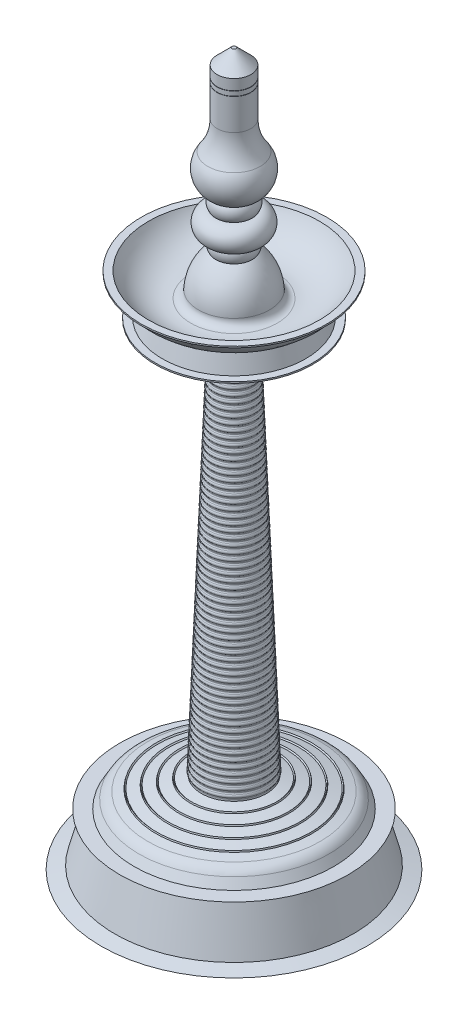
SolidWorks part; units mm, degrees
material "Brass"
ref_plane "Front Plane" through (0, 0, 0) normal (0, 0, 1) x (1, 0, 0)
ref_plane "Top Plane" through (0, 0, 0) normal (0, 1, 0) x (1, 0, 0)
ref_plane "Right Plane" through (0, 0, 0) normal (1, 0, 0) x (0, 0, -1)
sketch "Sketch1" plane through (0, 0, 0) normal (0, 0, 1) x (1, 0, 0)
  line L0 (0, 0) -> (0, 1500)
  line L1 (0, 0) -> (280, 0)
  line L2 (280, 0) -> (251.0222, 7.7646)
  line L3 (251.0222, 7.7646) -> (224.2273, 107.7646)
  line L4 (224.2273, 107.7646) -> (240.5603, 110.6445)
  line L5 (240.5603, 110.6445) -> (210.5603, 110.6445)
  line L6 (210.5603, 110.6445) -> (200.3028, 128.411)
  line L7 (182.0867, 142.3887) -> (164.0972, 147.209)
  line L8 (68.5193, 172.819) -> (68.3959, 176.1083)
  line L9 (37.3252, 1004.6625) -> (166.1634, 1004.6625)
  line L10 (166.1634, 1007.6625) -> (151.1634, 1007.6625)
  line L11 (166.1634, 1004.6625) -> (166.1634, 1007.6625)
  line L12 (151.1634, 1007.6625) -> (140.4454, 1047.6625)
  line L13 (187.6071, 1090.0058) -> (195.3379, 1090.0058)
  line L14 (75, 0) -> (68.3959, 176.1083) construction
  line L15 (195.3379, 1090.0058) -> (195.3379, 1093.0058)
  line L16 (195.3379, 1093.0058) -> (180.3379, 1093.0058)
  line L17 (164.0972, 147.209) -> (163.3207, 150.1068)
  line L18 (163.3207, 150.1068) -> (161.1994, 147.9855)
  line L19 (139.1726, 156.5773) -> (137.0513, 154.4559)
  line L20 (139.9491, 153.6795) -> (139.1726, 156.5773)
  line L21 (115.0245, 163.0477) -> (112.9031, 160.9264)
  line L22 (115.8009, 160.15) -> (115.0245, 163.0477)
  line L23 (90.8763, 169.5182) -> (88.755, 167.3969)
  line L24 (91.6528, 166.6204) -> (90.8763, 169.5182)
  line L25 (163.3207, 150.1068) -> (139.1726, 156.5773) construction
  line L26 (88.755, 167.3969) -> (68.5193, 172.819)
  line L27 (112.9031, 160.9264) -> (91.6528, 166.6204)
  line L28 (137.0513, 154.4559) -> (115.8009, 160.15)
  line L29 (161.1994, 147.9855) -> (139.9491, 153.6795)
  line L30 (0, 1500) -> (4.1464, 1500)
  line L31 (4.1464, 1500) -> (35.5592, 1468.5872)
  line L32 (35.5592, 1468.5872) -> (35.5592, 1446.3854)
  line L33 (37.3674, 1003.5367) -> (37.3252, 1004.6625)
  line L34 (37.4424, 1001.536) -> (0, 2000) construction
  line L35 (38.7061, 994.5731) -> (39.1839, 981.8321) construction
  line L36 (37.8452, 990.7957) -> (37.7424, 993.536) construction
  line L37 (37.8452, 990.7957) -> (37.8174, 991.5352)
  line L38 (38.323, 978.0547) -> (38.2952, 978.7941)
  line L39 (38.323, 978.0547) -> (38.2952, 978.7941) construction
  line L40 (38.8007, 965.3136) -> (38.773, 966.0531)
  line L41 (38.8007, 965.3136) -> (38.773, 966.0531) construction
  line L42 (39.2785, 952.5726) -> (39.2508, 953.312)
  line L43 (39.2785, 952.5726) -> (39.2508, 953.312) construction
  line L44 (39.7563, 939.8315) -> (39.7286, 940.571)
  line L45 (39.7563, 939.8315) -> (39.7286, 940.571) construction
  line L46 (40.2341, 927.0905) -> (40.2064, 927.83)
  line L47 (40.2341, 927.0905) -> (40.2064, 927.83) construction
  line L48 (40.7119, 914.3494) -> (40.6842, 915.0889) construction
  line L49 (40.7119, 914.3494) -> (40.6842, 915.0889)
  line L50 (41.1897, 901.6084) -> (41.162, 902.3479)
  line L51 (41.1897, 901.6084) -> (41.162, 902.3479) construction
  line L52 (41.6675, 888.8673) -> (41.6397, 889.6068)
  line L53 (41.6675, 888.8673) -> (41.6397, 889.6068) construction
  line L54 (42.1453, 876.1263) -> (42.1175, 876.8658) construction
  line L55 (42.1453, 876.1263) -> (42.1175, 876.8658)
  line L56 (42.6231, 863.3852) -> (42.5953, 864.1247)
  line L57 (42.6231, 863.3852) -> (42.5953, 864.1247) construction
  line L58 (43.1008, 850.6442) -> (43.0731, 851.3837)
  line L59 (43.1008, 850.6442) -> (43.0731, 851.3837) construction
  line L60 (43.5786, 837.9032) -> (43.5509, 838.6426) construction
  line L61 (43.5786, 837.9032) -> (43.5509, 838.6426)
  line L62 (44.0564, 825.1621) -> (44.0287, 825.9016) construction
  line L63 (44.0564, 825.1621) -> (44.0287, 825.9016)
  line L64 (44.5342, 812.4211) -> (44.5065, 813.1606) construction
  line L65 (44.5342, 812.4211) -> (44.5065, 813.1606)
  line L66 (45.012, 799.68) -> (44.9843, 800.4195)
  line L67 (45.012, 799.68) -> (44.9843, 800.4195) construction
  line L68 (45.4898, 786.939) -> (45.4621, 787.6785)
  line L69 (45.4898, 786.939) -> (45.4621, 787.6785) construction
  line L70 (45.9676, 774.1979) -> (45.9398, 774.9374) construction
  line L71 (45.9676, 774.1979) -> (45.9398, 774.9374)
  line L72 (46.4454, 761.4569) -> (46.4176, 762.1964)
  line L73 (46.4454, 761.4569) -> (46.4176, 762.1964) construction
  line L74 (46.9232, 748.7158) -> (46.8954, 749.4553)
  line L75 (46.9232, 748.7158) -> (46.8954, 749.4553) construction
  line L76 (47.4009, 735.9748) -> (47.3732, 736.7143)
  line L77 (47.4009, 735.9748) -> (47.3732, 736.7143) construction
  line L78 (47.8787, 723.2338) -> (47.851, 723.9732)
  line L79 (47.8787, 723.2338) -> (47.851, 723.9732) construction
  line L80 (48.3565, 710.4927) -> (48.3288, 711.2322)
  line L81 (48.3565, 710.4927) -> (48.3288, 711.2322) construction
  line L82 (48.8343, 697.7517) -> (48.8066, 698.4912)
  line L83 (48.8343, 697.7517) -> (48.8066, 698.4912) construction
  line L84 (49.3121, 685.0106) -> (49.2844, 685.7501)
  line L85 (49.3121, 685.0106) -> (49.2844, 685.7501) construction
  line L86 (49.7899, 672.2696) -> (49.7622, 673.0091) construction
  line L87 (49.7899, 672.2696) -> (49.7622, 673.0091)
  line L88 (50.2677, 659.5285) -> (50.2399, 660.268)
  line L89 (50.2677, 659.5285) -> (50.2399, 660.268) construction
  line L90 (50.7455, 646.7875) -> (50.7177, 647.527)
  line L91 (50.7455, 646.7875) -> (50.7177, 647.527) construction
  line L92 (51.2233, 634.0464) -> (51.1955, 634.7859)
  line L93 (51.2233, 634.0464) -> (51.1955, 634.7859) construction
  line L94 (51.701, 621.3054) -> (51.6733, 622.0449) construction
  line L95 (51.701, 621.3054) -> (51.6733, 622.0449)
  line L96 (52.1788, 608.5644) -> (52.1511, 609.3038)
  line L97 (52.1788, 608.5644) -> (52.1511, 609.3038) construction
  line L98 (52.6566, 595.8233) -> (52.6289, 596.5628)
  line L99 (52.6566, 595.8233) -> (52.6289, 596.5628) construction
  line L100 (53.1344, 583.0823) -> (53.1067, 583.8217)
  line L101 (53.1344, 583.0823) -> (53.1067, 583.8217) construction
  line L102 (53.6122, 570.3412) -> (53.5845, 571.0807)
  line L103 (53.6122, 570.3412) -> (53.5845, 571.0807) construction
  line L104 (54.09, 557.6002) -> (54.0623, 558.3397) construction
  line L105 (54.09, 557.6002) -> (54.0623, 558.3397)
  line L106 (54.5678, 544.8591) -> (54.5401, 545.5986) construction
  line L107 (54.5678, 544.8591) -> (54.5401, 545.5986)
  line L108 (55.0456, 532.1181) -> (55.0178, 532.8576)
  line L109 (55.0456, 532.1181) -> (55.0178, 532.8576) construction
  line L110 (55.5234, 519.377) -> (55.4956, 520.1165)
  line L111 (55.5234, 519.377) -> (55.4956, 520.1165) construction
  line L112 (56.0011, 506.636) -> (55.9734, 507.3755)
  line L113 (56.0011, 506.636) -> (55.9734, 507.3755) construction
  line L114 (56.4789, 493.895) -> (56.4512, 494.6344)
  line L115 (56.4789, 493.895) -> (56.4512, 494.6344) construction
  line L116 (56.9567, 481.1539) -> (56.929, 481.8934)
  line L117 (56.9567, 481.1539) -> (56.929, 481.8934) construction
  line L118 (57.4345, 468.4129) -> (57.4068, 469.1523) construction
  line L119 (57.4345, 468.4129) -> (57.4068, 469.1523)
  line L120 (57.9123, 455.6718) -> (57.8846, 456.4113) construction
  line L121 (57.9123, 455.6718) -> (57.8846, 456.4113)
  line L122 (58.3901, 442.9308) -> (58.3624, 443.6703) construction
  line L123 (58.3901, 442.9308) -> (58.3624, 443.6703)
  line L124 (58.8679, 430.1897) -> (58.8402, 430.9292) construction
  line L125 (58.8679, 430.1897) -> (58.8402, 430.9292)
  line L126 (59.3457, 417.4487) -> (59.3179, 418.1882)
  line L127 (59.3457, 417.4487) -> (59.3179, 418.1882) construction
  line L128 (59.8235, 404.7076) -> (59.7957, 405.4471) construction
  line L129 (59.8235, 404.7076) -> (59.7957, 405.4471)
  line L130 (60.3013, 391.9666) -> (60.2735, 392.7061) construction
  line L131 (60.3013, 391.9666) -> (60.2735, 392.7061)
  line L132 (60.779, 379.2256) -> (60.7513, 379.965) construction
  line L133 (60.779, 379.2256) -> (60.7513, 379.965)
  line L134 (61.2568, 366.4845) -> (61.2291, 367.224) construction
  line L135 (61.2568, 366.4845) -> (61.2291, 367.224)
  line L136 (61.7346, 353.7435) -> (61.7069, 354.4829)
  line L137 (61.7346, 353.7435) -> (61.7069, 354.4829) construction
  line L138 (62.2124, 341.0024) -> (62.1847, 341.7419) construction
  line L139 (62.2124, 341.0024) -> (62.1847, 341.7419)
  line L140 (62.6902, 328.2614) -> (62.6625, 329.0009) construction
  line L141 (62.6902, 328.2614) -> (62.6625, 329.0009)
  line L142 (63.168, 315.5203) -> (63.1403, 316.2598) construction
  line L143 (63.168, 315.5203) -> (63.1403, 316.2598)
  line L144 (63.6458, 302.7793) -> (63.618, 303.5188) construction
  line L145 (63.6458, 302.7793) -> (63.618, 303.5188)
  line L146 (64.1236, 290.0382) -> (64.0958, 290.7777) construction
  line L147 (64.1236, 290.0382) -> (64.0958, 290.7777)
  line L148 (64.6014, 277.2972) -> (64.5736, 278.0367) construction
  line L149 (64.6014, 277.2972) -> (64.5736, 278.0367)
  line L150 (65.0791, 264.5562) -> (65.0514, 265.2956) construction
  line L151 (65.0791, 264.5562) -> (65.0514, 265.2956)
  line L152 (65.5569, 251.8151) -> (65.5292, 252.5546)
  line L153 (65.5569, 251.8151) -> (65.5292, 252.5546) construction
  line L154 (66.0347, 239.0741) -> (66.007, 239.8135) construction
  line L155 (66.0347, 239.0741) -> (66.007, 239.8135)
  line L156 (66.5125, 226.333) -> (66.4848, 227.0725) construction
  line L157 (66.5125, 226.333) -> (66.4848, 227.0725)
  line L158 (66.9903, 213.592) -> (66.9626, 214.3315) construction
  line L159 (66.9903, 213.592) -> (66.9626, 214.3315)
  line L160 (67.9459, 188.1099) -> (67.9181, 188.8494) construction
  line L161 (67.9459, 188.1099) -> (67.9181, 188.8494)
  line L162 (67.4681, 200.8509) -> (67.4404, 201.5904) construction
  line L163 (67.4681, 200.8509) -> (67.4404, 201.5904)
  line L164 (35.5592, 1446.3854) -> (34.5983, 1446.1086)
  line L165 (34.5983, 1446.1086) -> (35.5592, 1445.8317)
  line L166 (35.5592, 1436.3854) -> (34.5983, 1436.1086)
  line L167 (34.5983, 1436.1086) -> (35.5592, 1435.8317)
  line L168 (35.5592, 1445.8317) -> (35.5592, 1436.3854) construction
  line L169 (35.5592, 1445.8317) -> (35.5592, 1436.3854)
  line L170 (35.5592, 1435.8317) -> (35.5592, 1369.9089)
  arc A0 (140.4454, 1047.6625) -> (187.6071, 1090.0058) centre (122.3281, 1115.2773) ccw
  arc A1 (200.3028, 128.411) -> (182.0867, 142.3887) centre (174.3221, 113.411) ccw
  arc A2 (55.0794, 1310.554) -> (37.3252, 1235.0425) centre (14.1154, 1280.3425) cw
  arc A3 (35.5592, 1369.9089) -> (55.0794, 1310.554) centre (135.5592, 1369.9089) ccw
  arc A4 (37.3252, 1235.0425) -> (38.0549, 1207.6096) centre (18.2342, 1220.8085) cw
  arc A5 (38.0549, 1207.6096) -> (38.3671, 1155.8588) centre (38.211, 1181.7342) cw
  arc A6 (38.3671, 1155.8588) -> (38.3671, 1132.1847) centre (17.118, 1144.0218) cw
  arc A7 (38.3671, 1132.1847) -> (75, 1058.7969) centre (-27.0346, 1053.7014) cw
  arc A8 (75, 1058.7969) -> (90.8763, 1042.3596) centre (91.1568, 1058.5164) ccw
  arc A9 (90.8763, 1042.3596) -> (180.3379, 1093.0058) centre (99.6879, 1131.1306) ccw
  arc A10 (38.4811, 1000.5739) -> (38.7061, 994.5731) centre (34.5983, 997.4237) cw
  arc A11 (38.7061, 994.5731) -> (37.8174, 991.5352) centre (42.8139, 991.7225) ccw
  arc A12 (38.4811, 1000.5739) -> (37.3674, 1003.5367) centre (42.3639, 1003.7241) cw
  arc A13 (39.1839, 981.8321) -> (38.2952, 978.7941) centre (43.2917, 978.9815) ccw
  arc A14 (38.9588, 987.8328) -> (39.1839, 981.8321) centre (35.076, 984.6826) cw
  arc A15 (38.9588, 987.8328) -> (37.8452, 990.7957) centre (42.8416, 990.9831) cw
  arc A16 (39.6617, 969.091) -> (38.773, 966.0531) centre (43.7695, 966.2405) ccw
  arc A17 (39.4366, 975.0918) -> (39.6617, 969.091) centre (35.5538, 971.9416) cw
  arc A18 (39.4366, 975.0918) -> (38.323, 978.0547) centre (43.3194, 978.242) cw
  arc A19 (40.1395, 956.35) -> (39.2508, 953.312) centre (44.2473, 953.4994) ccw
  arc A20 (39.9144, 962.3508) -> (40.1395, 956.35) centre (36.0316, 959.2005) cw
  arc A21 (39.9144, 962.3508) -> (38.8007, 965.3136) centre (43.7972, 965.501) cw
  arc A22 (40.6172, 943.6089) -> (39.7286, 940.571) centre (44.7251, 940.7584) ccw
  arc A23 (40.3922, 949.6097) -> (40.6172, 943.6089) centre (36.5094, 946.4595) cw
  arc A24 (40.3922, 949.6097) -> (39.2785, 952.5726) centre (44.275, 952.7599) cw
  arc A25 (41.095, 930.8679) -> (40.2064, 927.83) centre (45.2029, 928.0173) ccw
  arc A26 (40.87, 936.8687) -> (41.095, 930.8679) centre (36.9872, 933.7185) cw
  arc A27 (40.87, 936.8687) -> (39.7563, 939.8315) centre (44.7528, 940.0189) cw
  arc A28 (41.5728, 918.1268) -> (40.6842, 915.0889) centre (45.6807, 915.2763) ccw
  arc A29 (41.3478, 924.1276) -> (41.5728, 918.1268) centre (37.465, 920.9774) cw
  arc A30 (41.3478, 924.1276) -> (40.2341, 927.0905) centre (45.2306, 927.2778) cw
  arc A31 (42.0506, 905.3858) -> (41.162, 902.3479) centre (46.1584, 902.5352) ccw
  arc A32 (41.8256, 911.3866) -> (42.0506, 905.3858) centre (37.9428, 908.2364) cw
  arc A33 (41.8256, 911.3866) -> (40.7119, 914.3494) centre (45.7084, 914.5368) cw
  arc A34 (42.5284, 892.6448) -> (41.6397, 889.6068) centre (46.6362, 889.7942) ccw
  arc A35 (42.3034, 898.6455) -> (42.5284, 892.6448) centre (38.4206, 895.4953) cw
  arc A36 (42.3034, 898.6455) -> (41.1897, 901.6084) centre (46.1862, 901.7958) cw
  arc A37 (43.0062, 879.9037) -> (42.1175, 876.8658) centre (47.114, 877.0531) ccw
  arc A38 (42.7812, 885.9045) -> (43.0062, 879.9037) centre (38.8984, 882.7543) cw
  arc A39 (42.7812, 885.9045) -> (41.6675, 888.8673) centre (46.664, 889.0547) cw
  arc A40 (43.484, 867.1627) -> (42.5953, 864.1247) centre (47.5918, 864.3121) ccw
  arc A41 (43.259, 873.1634) -> (43.484, 867.1627) centre (39.3762, 870.0132) cw
  arc A42 (43.259, 873.1634) -> (42.1453, 876.1263) centre (47.1418, 876.3137) cw
  arc A43 (43.9618, 854.4216) -> (43.0731, 851.3837) centre (48.0696, 851.5711) ccw
  arc A44 (43.7367, 860.4224) -> (43.9618, 854.4216) centre (39.8539, 857.2722) cw
  arc A45 (43.7367, 860.4224) -> (42.6231, 863.3852) centre (47.6195, 863.5726) cw
  arc A46 (44.4396, 841.6806) -> (43.5509, 838.6426) centre (48.5474, 838.83) ccw
  arc A47 (44.2145, 847.6814) -> (44.4396, 841.6806) centre (40.3317, 844.5311) cw
  arc A48 (44.2145, 847.6814) -> (43.1008, 850.6442) centre (48.0973, 850.8316) cw
  arc A49 (44.9173, 828.9395) -> (44.0287, 825.9016) centre (49.0252, 826.089) ccw
  arc A50 (44.6923, 834.9403) -> (44.9173, 828.9395) centre (40.8095, 831.7901) cw
  arc A51 (44.6923, 834.9403) -> (43.5786, 837.9032) centre (48.5751, 838.0905) cw
  arc A52 (45.3951, 816.1985) -> (44.5065, 813.1606) centre (49.503, 813.3479) ccw
  arc A53 (45.1701, 822.1993) -> (45.3951, 816.1985) centre (41.2873, 819.0491) cw
  arc A54 (45.1701, 822.1993) -> (44.0564, 825.1621) centre (49.0529, 825.3495) cw
  arc A55 (45.8729, 803.4574) -> (44.9843, 800.4195) centre (49.9808, 800.6069) ccw
  arc A56 (45.6479, 809.4582) -> (45.8729, 803.4574) centre (41.7651, 806.308) cw
  arc A57 (45.6479, 809.4582) -> (44.5342, 812.4211) centre (49.5307, 812.6084) cw
  arc A58 (46.3507, 790.7164) -> (45.4621, 787.6785) centre (50.4585, 787.8658) ccw
  arc A59 (46.1257, 796.7172) -> (46.3507, 790.7164) centre (42.2429, 793.567) cw
  arc A60 (46.1257, 796.7172) -> (45.012, 799.68) centre (50.0085, 799.8674) cw
  arc A61 (46.8285, 777.9754) -> (45.9398, 774.9374) centre (50.9363, 775.1248) ccw
  arc A62 (46.6035, 783.9761) -> (46.8285, 777.9754) centre (42.7207, 780.8259) cw
  arc A63 (46.6035, 783.9761) -> (45.4898, 786.939) centre (50.4863, 787.1264) cw
  arc A64 (47.3063, 765.2343) -> (46.4176, 762.1964) centre (51.4141, 762.3837) ccw
  arc A65 (47.0813, 771.2351) -> (47.3063, 765.2343) centre (43.1985, 768.0849) cw
  arc A66 (47.0813, 771.2351) -> (45.9676, 774.1979) centre (50.9641, 774.3853) cw
  arc A67 (47.7841, 752.4933) -> (46.8954, 749.4553) centre (51.8919, 749.6427) ccw
  arc A68 (47.5591, 758.494) -> (47.7841, 752.4933) centre (43.6763, 755.3438) cw
  arc A69 (47.5591, 758.494) -> (46.4454, 761.4569) centre (51.4419, 761.6443) cw
  arc A70 (48.2619, 739.7522) -> (47.3732, 736.7143) centre (52.3697, 736.9017) ccw
  arc A71 (48.0368, 745.753) -> (48.2619, 739.7522) centre (44.154, 742.6028) cw
  arc A72 (48.0368, 745.753) -> (46.9232, 748.7158) centre (51.9196, 748.9032) cw
  arc A73 (48.7397, 727.0112) -> (47.851, 723.9732) centre (52.8475, 724.1606) ccw
  arc A74 (48.5146, 733.012) -> (48.7397, 727.0112) centre (44.6318, 729.8617) cw
  arc A75 (48.5146, 733.012) -> (47.4009, 735.9748) centre (52.3974, 736.1622) cw
  arc A76 (49.2175, 714.2701) -> (48.3288, 711.2322) centre (53.3253, 711.4196) ccw
  arc A77 (48.9924, 720.2709) -> (49.2175, 714.2701) centre (45.1096, 717.1207) cw
  arc A78 (48.9924, 720.2709) -> (47.8787, 723.2338) centre (52.8752, 723.4211) cw
  arc A79 (49.6952, 701.5291) -> (48.8066, 698.4912) centre (53.8031, 698.6785) ccw
  arc A80 (49.4702, 707.5299) -> (49.6952, 701.5291) centre (45.5874, 704.3797) cw
  arc A81 (49.4702, 707.5299) -> (48.3565, 710.4927) centre (53.353, 710.6801) cw
  arc A82 (50.173, 688.788) -> (49.2844, 685.7501) centre (54.2809, 685.9375) ccw
  arc A83 (49.948, 694.7888) -> (50.173, 688.788) centre (46.0652, 691.6386) cw
  arc A84 (49.948, 694.7888) -> (48.8343, 697.7517) centre (53.8308, 697.939) cw
  arc A85 (50.6508, 676.047) -> (49.7622, 673.0091) centre (54.7586, 673.1964) ccw
  arc A86 (50.4258, 682.0478) -> (50.6508, 676.047) centre (46.543, 678.8976) cw
  arc A87 (50.4258, 682.0478) -> (49.3121, 685.0106) centre (54.3086, 685.198) cw
  arc A88 (51.1286, 663.306) -> (50.2399, 660.268) centre (55.2364, 660.4554) ccw
  arc A89 (50.9036, 669.3067) -> (51.1286, 663.306) centre (47.0208, 666.1565) cw
  arc A90 (50.9036, 669.3067) -> (49.7899, 672.2696) centre (54.7864, 672.4569) cw
  arc A91 (51.6064, 650.5649) -> (50.7177, 647.527) centre (55.7142, 647.7143) ccw
  arc A92 (51.3814, 656.5657) -> (51.6064, 650.5649) centre (47.4986, 653.4155) cw
  arc A93 (51.3814, 656.5657) -> (50.2677, 659.5285) centre (55.2642, 659.7159) cw
  arc A94 (52.0842, 637.8239) -> (51.1955, 634.7859) centre (56.192, 634.9733) ccw
  arc A95 (51.8592, 643.8246) -> (52.0842, 637.8239) centre (47.9764, 640.6744) cw
  arc A96 (51.8592, 643.8246) -> (50.7455, 646.7875) centre (55.742, 646.9749) cw
  arc A97 (52.562, 625.0828) -> (51.6733, 622.0449) centre (56.6698, 622.2323) ccw
  arc A98 (52.3369, 631.0836) -> (52.562, 625.0828) centre (48.4541, 627.9334) cw
  arc A99 (52.3369, 631.0836) -> (51.2233, 634.0464) centre (56.2197, 634.2338) cw
  arc A100 (53.0398, 612.3418) -> (52.1511, 609.3038) centre (57.1476, 609.4912) ccw
  arc A101 (52.8147, 618.3426) -> (53.0398, 612.3418) centre (48.9319, 615.1923) cw
  arc A102 (52.8147, 618.3426) -> (51.701, 621.3054) centre (56.6975, 621.4928) cw
  arc A103 (53.5176, 599.6007) -> (52.6289, 596.5628) centre (57.6254, 596.7502) ccw
  arc A104 (53.2925, 605.6015) -> (53.5176, 599.6007) centre (49.4097, 602.4513) cw
  arc A105 (53.2925, 605.6015) -> (52.1788, 608.5644) centre (57.1753, 608.7517) cw
  arc A106 (53.9953, 586.8597) -> (53.1067, 583.8217) centre (58.1032, 584.0091) ccw
  arc A107 (53.7703, 592.8605) -> (53.9953, 586.8597) centre (49.8875, 589.7103) cw
  arc A108 (53.7703, 592.8605) -> (52.6566, 595.8233) centre (57.6531, 596.0107) cw
  arc A109 (54.4731, 574.1186) -> (53.5845, 571.0807) centre (58.581, 571.2681) ccw
  arc A110 (54.2481, 580.1194) -> (54.4731, 574.1186) centre (50.3653, 576.9692) cw
  arc A111 (54.2481, 580.1194) -> (53.1344, 583.0823) centre (58.1309, 583.2696) cw
  arc A112 (54.9509, 561.3776) -> (54.0623, 558.3397) centre (59.0588, 558.527) ccw
  arc A113 (54.7259, 567.3784) -> (54.9509, 561.3776) centre (50.8431, 564.2282) cw
  arc A114 (54.7259, 567.3784) -> (53.6122, 570.3412) centre (58.6087, 570.5286) cw
  arc A115 (55.4287, 548.6366) -> (54.5401, 545.5986) centre (59.5365, 545.786) ccw
  arc A116 (55.2037, 554.6373) -> (55.4287, 548.6366) centre (51.3209, 551.4871) cw
  arc A117 (55.2037, 554.6373) -> (54.09, 557.6002) centre (59.0865, 557.7875) cw
  arc A118 (55.9065, 535.8955) -> (55.0178, 532.8576) centre (60.0143, 533.0449) ccw
  arc A119 (55.6815, 541.8963) -> (55.9065, 535.8955) centre (51.7987, 538.7461) cw
  arc A120 (55.6815, 541.8963) -> (54.5678, 544.8591) centre (59.5643, 545.0465) cw
  arc A121 (56.3843, 523.1545) -> (55.4956, 520.1165) centre (60.4921, 520.3039) ccw
  arc A122 (56.1593, 529.1552) -> (56.3843, 523.1545) centre (52.2765, 526.005) cw
  arc A123 (56.1593, 529.1552) -> (55.0456, 532.1181) centre (60.0421, 532.3055) cw
  arc A124 (56.8621, 510.4134) -> (55.9734, 507.3755) centre (60.9699, 507.5628) ccw
  arc A125 (56.637, 516.4142) -> (56.8621, 510.4134) centre (52.7542, 513.264) cw
  arc A126 (56.637, 516.4142) -> (55.5234, 519.377) centre (60.5198, 519.5644) cw
  arc A127 (57.3399, 497.6724) -> (56.4512, 494.6344) centre (61.4477, 494.8218) ccw
  arc A128 (57.1148, 503.6732) -> (57.3399, 497.6724) centre (53.232, 500.5229) cw
  arc A129 (57.1148, 503.6732) -> (56.0011, 506.636) centre (60.9976, 506.8234) cw
  arc A130 (57.8177, 484.9313) -> (56.929, 481.8934) centre (61.9255, 482.0808) ccw
  arc A131 (57.5926, 490.9321) -> (57.8177, 484.9313) centre (53.7098, 487.7819) cw
  arc A132 (57.5926, 490.9321) -> (56.4789, 493.895) centre (61.4754, 494.0823) cw
  arc A133 (58.2954, 472.1903) -> (57.4068, 469.1523) centre (62.4033, 469.3397) ccw
  arc A134 (58.0704, 478.1911) -> (58.2954, 472.1903) centre (54.1876, 475.0408) cw
  arc A135 (58.0704, 478.1911) -> (56.9567, 481.1539) centre (61.9532, 481.3413) cw
  arc A136 (58.7732, 459.4492) -> (57.8846, 456.4113) centre (62.8811, 456.5987) ccw
  arc A137 (58.5482, 465.45) -> (58.7732, 459.4492) centre (54.6654, 462.2998) cw
  arc A138 (58.5482, 465.45) -> (57.4345, 468.4129) centre (62.431, 468.6002) cw
  arc A139 (59.251, 446.7082) -> (58.3624, 443.6703) centre (63.3589, 443.8576) ccw
  arc A140 (59.026, 452.709) -> (59.251, 446.7082) centre (55.1432, 449.5588) cw
  arc A141 (59.026, 452.709) -> (57.9123, 455.6718) centre (62.9088, 455.8592) cw
  arc A142 (59.7288, 433.9671) -> (58.8402, 430.9292) centre (63.8366, 431.1166) ccw
  arc A143 (59.5038, 439.9679) -> (59.7288, 433.9671) centre (55.621, 436.8177) cw
  arc A144 (59.5038, 439.9679) -> (58.3901, 442.9308) centre (63.3866, 443.1181) cw
  arc A145 (60.2066, 421.2261) -> (59.3179, 418.1882) centre (64.3144, 418.3755) ccw
  arc A146 (59.9816, 427.2269) -> (60.2066, 421.2261) centre (56.0988, 424.0767) cw
  arc A147 (59.9816, 427.2269) -> (58.8679, 430.1897) centre (63.8644, 430.3771) cw
  arc A148 (60.6844, 408.4851) -> (59.7957, 405.4471) centre (64.7922, 405.6345) ccw
  arc A149 (60.4594, 414.4858) -> (60.6844, 408.4851) centre (56.5766, 411.3356) cw
  arc A150 (60.4594, 414.4858) -> (59.3457, 417.4487) centre (64.3422, 417.6361) cw
  arc A151 (61.1622, 395.744) -> (60.2735, 392.7061) centre (65.27, 392.8934) ccw
  arc A152 (60.9372, 401.7448) -> (61.1622, 395.744) centre (57.0543, 398.5946) cw
  arc A153 (60.9372, 401.7448) -> (59.8235, 404.7076) centre (64.82, 404.895) cw
  arc A154 (61.64, 383.003) -> (60.7513, 379.965) centre (65.7478, 380.1524) ccw
  arc A155 (61.4149, 389.0038) -> (61.64, 383.003) centre (57.5321, 385.8535) cw
  arc A156 (61.4149, 389.0038) -> (60.3013, 391.9666) centre (65.2977, 392.154) cw
  arc A157 (62.1178, 370.2619) -> (61.2291, 367.224) centre (66.2256, 367.4114) ccw
  arc A158 (61.8927, 376.2627) -> (62.1178, 370.2619) centre (58.0099, 373.1125) cw
  arc A159 (61.8927, 376.2627) -> (60.779, 379.2256) centre (65.7755, 379.4129) cw
  arc A160 (62.5955, 357.5209) -> (61.7069, 354.4829) centre (66.7034, 354.6703) ccw
  arc A161 (62.3705, 363.5217) -> (62.5955, 357.5209) centre (58.4877, 360.3714) cw
  arc A162 (62.3705, 363.5217) -> (61.2568, 366.4845) centre (66.2533, 366.6719) cw
  arc A163 (63.0733, 344.7798) -> (62.1847, 341.7419) centre (67.1812, 341.9293) ccw
  arc A164 (62.8483, 350.7806) -> (63.0733, 344.7798) centre (58.9655, 347.6304) cw
  arc A165 (62.8483, 350.7806) -> (61.7346, 353.7435) centre (66.7311, 353.9308) cw
  arc A166 (63.5511, 332.0388) -> (62.6625, 329.0009) centre (67.659, 329.1882) ccw
  arc A167 (63.3261, 338.0396) -> (63.5511, 332.0388) centre (59.4433, 334.8894) cw
  arc A168 (63.3261, 338.0396) -> (62.2124, 341.0024) centre (67.2089, 341.1898) cw
  arc A169 (64.0289, 319.2977) -> (63.1403, 316.2598) centre (68.1367, 316.4472) ccw
  arc A170 (63.8039, 325.2985) -> (64.0289, 319.2977) centre (59.9211, 322.1483) cw
  arc A171 (63.8039, 325.2985) -> (62.6902, 328.2614) centre (67.6867, 328.4487) cw
  arc A172 (64.5067, 306.5567) -> (63.618, 303.5188) centre (68.6145, 303.7061) ccw
  arc A173 (64.2817, 312.5575) -> (64.5067, 306.5567) centre (60.3989, 309.4073) cw
  arc A174 (64.2817, 312.5575) -> (63.168, 315.5203) centre (68.1645, 315.7077) cw
  arc A175 (64.9845, 293.8157) -> (64.0958, 290.7777) centre (69.0923, 290.9651) ccw
  arc A176 (64.7595, 299.8164) -> (64.9845, 293.8157) centre (60.8767, 296.6662) cw
  arc A177 (64.7595, 299.8164) -> (63.6458, 302.7793) centre (68.6423, 302.9667) cw
  arc A178 (65.4623, 281.0746) -> (64.5736, 278.0367) centre (69.5701, 278.224) ccw
  arc A179 (65.2373, 287.0754) -> (65.4623, 281.0746) centre (61.3545, 283.9252) cw
  arc A180 (65.2373, 287.0754) -> (64.1236, 290.0382) centre (69.1201, 290.2256) cw
  arc A181 (65.9401, 268.3336) -> (65.0514, 265.2956) centre (70.0479, 265.483) ccw
  arc A182 (65.715, 274.3344) -> (65.9401, 268.3336) centre (61.8322, 271.1841) cw
  arc A183 (65.715, 274.3344) -> (64.6014, 277.2972) centre (69.5978, 277.4846) cw
  arc A184 (66.4179, 255.5925) -> (65.5292, 252.5546) centre (70.5257, 252.742) ccw
  arc A185 (66.1928, 261.5933) -> (66.4179, 255.5925) centre (62.31, 258.4431) cw
  arc A186 (66.1928, 261.5933) -> (65.0791, 264.5562) centre (70.0756, 264.7435) cw
  arc A187 (66.8956, 242.8515) -> (66.007, 239.8135) centre (71.0035, 240.0009) ccw
  arc A188 (66.6706, 248.8523) -> (66.8956, 242.8515) centre (62.7878, 245.702) cw
  arc A189 (66.6706, 248.8523) -> (65.5569, 251.8151) centre (70.5534, 252.0025) cw
  arc A190 (67.3734, 230.1104) -> (66.4848, 227.0725) centre (71.4813, 227.2599) ccw
  arc A191 (67.1484, 236.1112) -> (67.3734, 230.1104) centre (63.2656, 232.961) cw
  arc A192 (67.1484, 236.1112) -> (66.0347, 239.0741) centre (71.0312, 239.2614) cw
  arc A193 (67.8512, 217.3694) -> (66.9626, 214.3315) centre (71.9591, 214.5188) ccw
  arc A194 (67.6262, 223.3702) -> (67.8512, 217.3694) centre (63.7434, 220.22) cw
  arc A195 (67.6262, 223.3702) -> (66.5125, 226.333) centre (71.509, 226.5204) cw
  arc A196 (68.329, 204.6283) -> (67.4404, 201.5904) centre (72.4368, 201.7778) ccw
  arc A197 (68.104, 210.6291) -> (68.329, 204.6283) centre (64.2212, 207.4789) cw
  arc A198 (68.104, 210.6291) -> (66.9903, 213.592) centre (71.9868, 213.7793) cw
  arc A199 (68.8068, 191.8873) -> (67.9181, 188.8494) centre (72.9146, 189.0367) ccw
  arc A200 (68.5818, 197.8881) -> (68.8068, 191.8873) centre (64.699, 194.7379) cw
  arc A201 (68.5818, 197.8881) -> (67.4681, 200.8509) centre (72.4646, 201.0383) cw
  arc A202 (69.2846, 179.1463) -> (68.3959, 176.1083) centre (73.3924, 176.2957) ccw
  arc A203 (69.0596, 185.147) -> (69.2846, 179.1463) centre (65.1768, 181.9968) cw
  arc A204 (69.0596, 185.147) -> (67.9459, 188.1099) centre (72.9424, 188.2973) cw
  point P17 (75, 0)
  point P519 (38.3671, 1132.1847)
  point P520 (38.211, 1207.6096)
  dimension "D9" = 70
  dimension "D18" = 30
  dimension "D22" = 100
  dimension "D23" = 5
  dimension "D24" = 5
  dimension "D1" = 1500
  dimension "D2" = 280
  dimension "D3" = 75
  dimension "D4" = 2000
  dimension "D5" = 3
  dimension "D6" = 3
  dimension "D7" = 15
  dimension "D8" = 15
  dimension "D10" = 40
  dimension "D11" = 15
  dimension "D12" = 120
  dimension "D13" = 85
  dimension "D14" = 100
  dimension "D15" = 120
  dimension "D16" = 30
  dimension "D17" = 30
  dimension "D19" = 3
  dimension "D20" = 3
  dimension "D21" = 25
  dimension "D26" = 12.75
  dimension "D27" = 1
  dimension "D25" = 4
revolve "Revolve1" add sketch "Sketch1" angle 360 about L0
